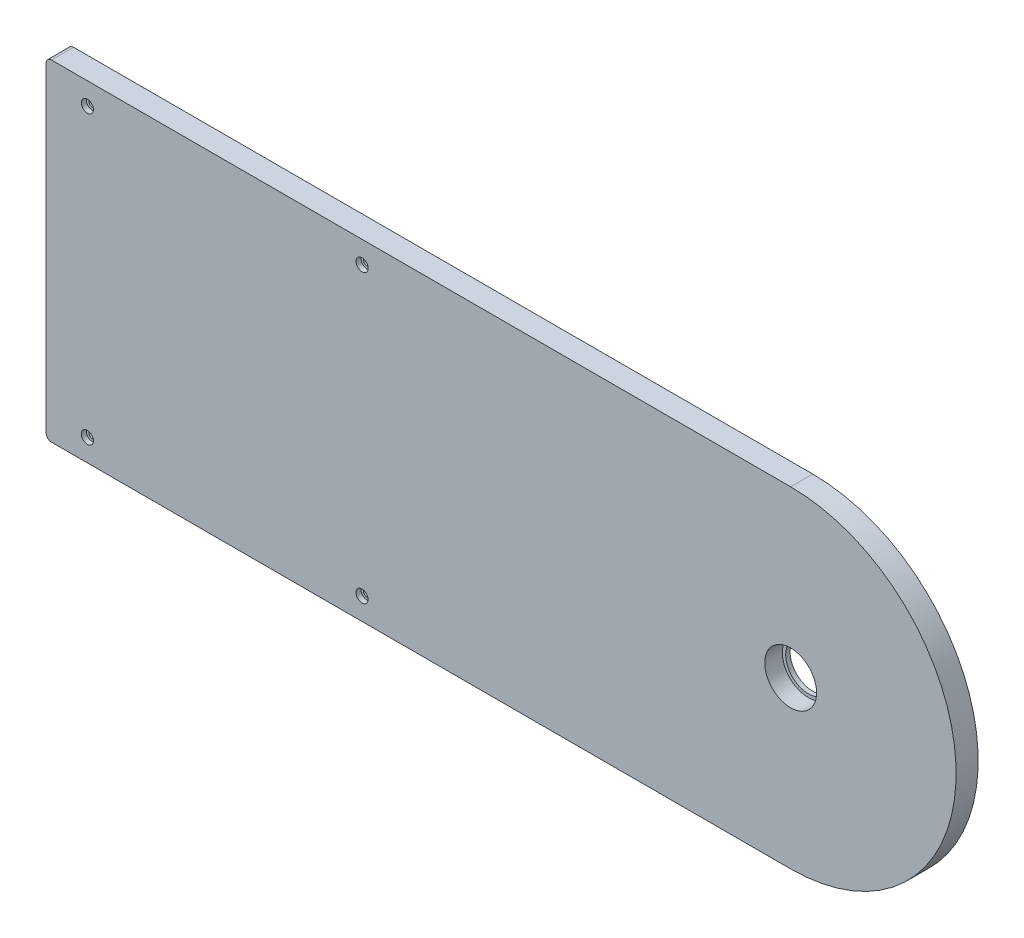
SolidWorks part; units mm, degrees
material "5052-H32"
ref_plane "Front Plane" through (0, 0, 0) normal (0, 0, 1) x (1, 0, 0)
ref_plane "Top Plane" through (0, 0, 0) normal (0, 1, 0) x (1, 0, 0)
ref_plane "Right Plane" through (0, 0, 0) normal (1, 0, 0) x (0, 0, -1)
sketch "Sketch1" plane through (0, 0, 0) normal (0, 0, 1) x (1, 0, 0)
  line L0 (0, 150) -> (-675, 150)
  line L1 (-675, 150) -> (-675, -150)
  line L2 (-675, -150) -> (0, -150)
  arc A1 (0, -150) -> (0, 150) centre (0, 0) ccw
  circle A2 centre (0, 0) radius 20.5
  dimension "D2" = 41
  dimension "D1" = 300
  dimension "D3" = 675
  dimension "D4" = 0
extrude "Boss-Extrude1" add sketch "Sketch1" along normal blind 20
sketch "Sketch2" plane through (0, 0, 20) normal (0, 0, 1) x (1, 0, 0)
  circle A0 centre (0, 0) radius 23.5
  dimension "D1" = 47
extrude "Cut-Extrude1" cut sketch "Sketch2" against normal blind 16
sketch "Sketch4" plane through (0, 0, 0) normal (0, 0, -1) x (-1, 0, 0)
  line L0 (675, 150) -> (675, -150) construction
  line L1 (675, -134) -> (356.25, -134)
  line L2 (675, -134) -> (675, -126)
  line L3 (675, -126) -> (356.25, -126)
  line L4 (356.25, -134) -> (356.25, -126)
  line L6 (675, 126) -> (356.25, 126)
  line L7 (675, 126) -> (675, 134)
  line L8 (675, 134) -> (356.25, 134)
  line L9 (356.25, 126) -> (356.25, 134)
  point P10 (675, 130)
  point P11 (675, -130)
  point P12 (356.25, 130)
  dimension "D1" = 8
  dimension "D2" = 8
  dimension "D3" = 260
  dimension "D4" = 130
  dimension "D5" = 318.75
extrude "Boss-Extrude2" add sketch "Sketch4" along normal blind 3
sketch "Sketch3" plane through (0, 0, 20) normal (0, 0, 1) x (1, 0, 0)
  line L0 (-675, 150) -> (-675, -150) construction
  circle A0 centre (-388.5, 130) radius 3.25
  circle A1 centre (-637.5, 130) radius 3.25
  circle A2 centre (-637.5, -130) radius 3.25
  circle A3 centre (-388.5, -130) radius 3.25
  dimension "D5" = 6.5
  dimension "D1" = 260
  dimension "D2" = 130
  dimension "D3" = 37.5
  dimension "D4" = 249
extrude "Cut-Extrude2" cut sketch "Sketch3" against normal through all
sketch "Sketch5" plane through (0, 0, 20) normal (0, 0, 1) x (1, 0, 0)
  circle A0 centre (-637.5, 130) radius 5.5
  circle A1 centre (-388.5, 130) radius 5.5
  circle A2 centre (-388.5, -130) radius 5.5
  circle A3 centre (-637.5, -130) radius 5.5
  dimension "D1" = 11
extrude "Cut-Extrude3" cut sketch "Sketch5" against normal blind 4.5
fillet "Fillet1" radius 5 2 edges at (-675, 150, 10) (-675, -150, 10)
